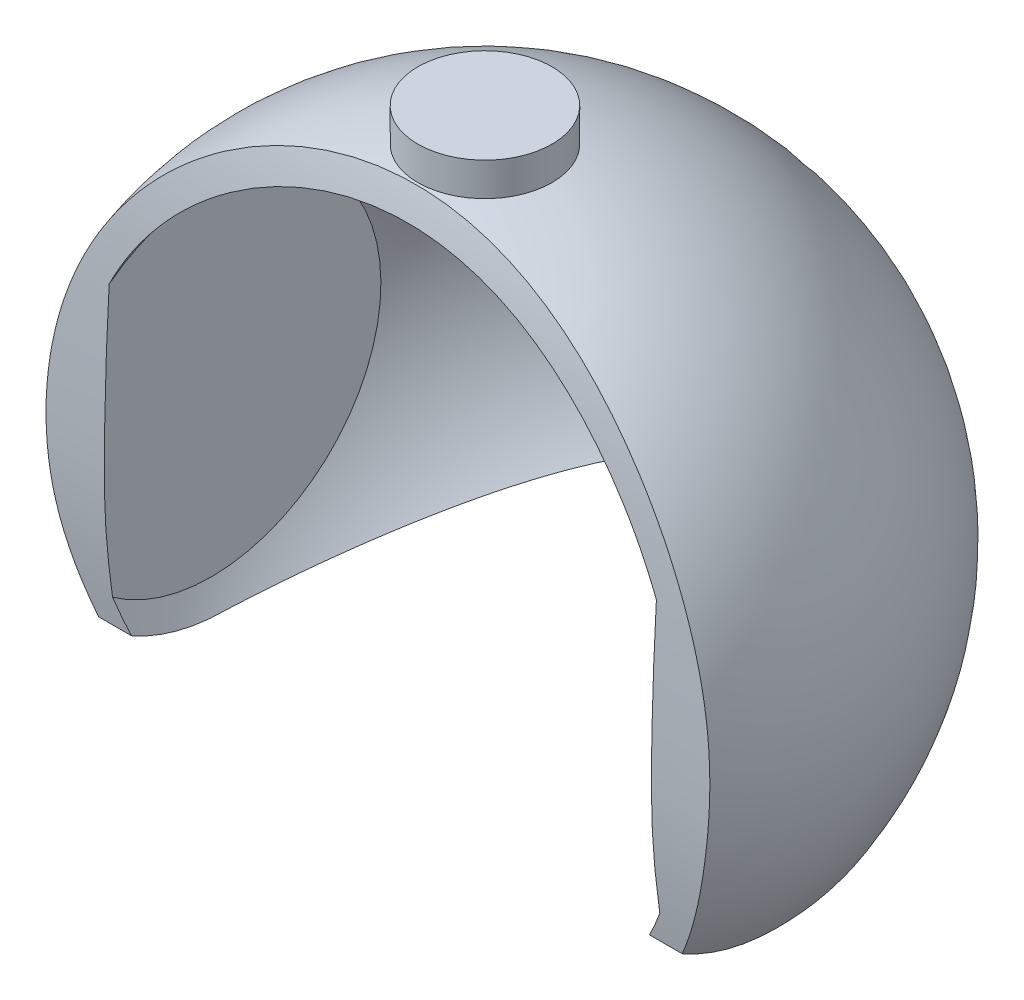
SolidWorks part; units mm, degrees
ref_plane "前视基准面" through (0, 0, 0) normal (0, 0, 1) x (1, 0, 0)
ref_plane "上视基准面" through (0, 0, 0) normal (0, 1, 0) x (1, 0, 0)
ref_plane "右视基准面" through (0, 0, 0) normal (1, 0, 0) x (0, 0, -1)
sketch "草图1" plane through (0, 0, 0) normal (0, 0, 1) x (1, 0, 0)
  line L0 (0, 0) -> (65, 0) construction
  line L1 (0, 0) -> (-65, 0) construction
  line L2 (65, 0) -> (-65, 0)
  arc A0 (65, 0) -> (-65, 0) centre (0, 0) ccw
  dimension "D1" = 130
revolve "旋转1" add sketch "草图1" angle 360 about L2
sketch "草图2" plane through (0, 0, 0) normal (1, 0, 0) x (0, 0, -1)
  circle A0 centre (0, 0) radius 65 construction
  arc A1 (-12.8963, 63.7078) -> (-12.8963, -63.7078) centre (0, 0) ccw
  spline S0 degree 3 poles (-12.8963, 63.7078) (-18.0688, 46.449) (-19.3163, 24.9438) (-20.0393, -0.9445) (-19.8545, -25.9273) (-14.0767, -46.8636) (-12.8963, -63.7078) knots 0 0 0 0 0.4176 0.500367 0.605328 1 1 1 1
extrude "切除-拉伸1" cut sketch "草图2" against normal mid plane 371
sketch "草图3" plane through (0, 0, 0) normal (0, 0, 1) x (1, 0, 0)
  line L0 (-61.8603, 0) -> (0, 0) construction
  line L1 (0, 0) -> (61.8603, 0) construction
  line L2 (51, 0) -> (51, 31.607)
  line L3 (0, 0) -> (0, 27.5389) construction
  line L4 (-51, 0) -> (-51, 31.607)
  line L5 (-51, 0) -> (51, 0)
  arc A0 (51, 31.607) -> (-51, 31.607) centre (0, 0) ccw
  spline S0 degree 3 poles (4.1719, 63.7078) (-4.1719, 63.7078) (-8.2647, 63.2762) (-14.2923, 62.0132) (-16.2827, 61.4887) (-19.24, 60.5436) (-20.2228, 60.2013) (-22.1571, 59.4713) (-23.111, 59.0829) (-27.8166, 57.027) (-31.3776, 55.0203) (-35.5847, 52.0644) (-36.4146, 51.4499) (-38.0458, 50.178) (-38.8424, 49.5243) (-41.177, 47.511) (-42.6598, 46.0995) (-45.4829, 43.141) (-46.8233, 41.5941) (-48.7269, 39.1715) (-49.3435, 38.3469) (-50.5407, 36.6631) (-51.1226, 35.8015) (-53.9156, 31.4438) (-55.7898, 27.7915) (-58.0721, 22.0703) (-58.744, 20.1224) (-59.6133, 17.1375) (-59.8805, 16.1293) (-60.363, 14.1103) (-60.5786, 13.0986) (-61.5302, 8.0293) (-61.8873, 3.939) (-61.8523, -1.2168) (-61.821, -2.2501) (-61.7104, -4.3211) (-61.6308, -5.3615) (-61.3231, -8.461) (-61.0268, -10.503) (-59.8852, -16.5579) (-58.794, -20.5006) (-56.9618, -25.3084) (-56.5706, -26.2662) (-55.747, -28.1513) (-55.3142, -29.08) (-53.9525, -31.8251) (-52.9605, -33.6007) (-50.8047, -37.0439) (-49.6409, -38.7116) (-47.7612, -41.1308) (-47.1123, -41.9234) (-45.7686, -43.4807) (-45.0714, -44.2476) (-41.5028, -47.9736) (-38.3823, -50.6178) (-33.3157, -54.0957) (-31.5621, -55.173) (-28.8323, -56.6625) (-27.9042, -57.1385) (-26.0361, -58.0371) (-25.0937, -58.4612) (-20.341, -60.4582) (-16.4095, -61.6643) (-11.3351, -62.6842) (-10.3108, -62.8638) (-8.2515, -63.1719) (-7.2222, -63.2996) (-4.1351, -63.6057) (-2.0783, -63.7071) (2.0329, -63.7085) (4.0873, -63.6086) (7.1671, -63.3059) (8.1934, -63.1795) (10.2453, -62.8746) (11.2737, -62.6955) (16.3646, -61.6773) (20.295, -60.4729) (25.979, -58.0915) (27.8381, -57.2012) (30.5713, -55.7153) (31.4741, -55.1941) (33.2394, -54.1135) (34.1046, -53.5528) (38.3446, -50.6489) (41.4635, -48.0074) (45.0185, -44.3047) (45.7121, -43.5439) (47.0643, -41.9811) (47.7186, -41.1838) (49.6103, -38.7544) (50.7798, -37.0812) (52.944, -33.6296) (53.9385, -31.8513) (55.3025, -29.1046) (55.7358, -28.1758) (56.56, -26.2915) (56.9516, -25.3338) (58.7878, -20.5217) (59.881, -16.5757) (61.0247, -10.516) (61.3216, -8.4725) (61.63, -5.3708) (61.7098, -4.3307) (61.8206, -2.2603) (61.852, -1.2272) (61.8879, 3.9274) (61.5317, 8.0175) (60.5808, 13.0876) (60.3654, 14.0995) (59.8832, 16.1189) (59.6161, 17.1274) (58.7471, 20.113) (58.0753, 22.0613) (55.7934, 27.7839) (53.9194, 31.4372) (51.1262, 35.7961) (50.5442, 36.6579) (49.3473, 38.3418) (48.7308, 39.1663) (46.8282, 41.5882) (45.489, 43.1342) (42.6693, 46.0901) (41.1888, 47.5) (38.8589, 49.5105) (38.0641, 50.1632) (36.4369, 51.4331) (35.6039, 52.0504) (31.3913, 55.0125) (27.8345, 57.0164) (22.2126, 59.4768) (20.2906, 60.2054) (17.3311, 61.1548) (16.3313, 61.4473) (14.3291, 61.9772) (13.3238, 62.2155) (8.2766, 63.2759) (4.1719, 63.7078) (-4.1719, 63.7078) (-8.2647, 63.2762) knots -0.03125 -0.03125 0 0 0.03125 0.03125 0.046875 0.046875 0.054687 0.054687 0.0625 0.0625 0.09375 0.09375 0.101562 0.101562 0.109375 0.109375 0.125 0.125 0.140625 0.140625 0.148437 0.148437 0.15625 0.15625 0.1875 0.1875 0.203125 0.203125 0.210937 0.210937 0.21875 0.21875 0.25 0.25 0.257812 0.257812 0.265625 0.265625 0.28125 0.28125 0.3125 0.3125 0.320312 0.320312 0.328125 0.328125 0.34375 0.34375 0.359375 0.359375 0.367187 0.367187 0.375 0.375 0.40625 0.40625 0.421875 0.421875 0.429687 0.429687 0.4375 0.4375 0.46875 0.46875 0.476562 0.476562 0.484375 0.484375 0.5 0.5 0.515625 0.515625 0.523437 0.523437 0.53125 0.53125 0.5625 0.5625 0.578125 0.578125 0.585937 0.585937 0.59375 0.59375 0.625 0.625 0.632812 0.632812 0.640625 0.640625 0.65625 0.65625 0.671875 0.671875 0.679687 0.679687 0.6875 0.6875 0.71875 0.71875 0.734375 0.734375 0.742187 0.742187 0.75 0.75 0.78125 0.78125 0.789062 0.789062 0.796875 0.796875 0.8125 0.8125 0.84375 0.84375 0.851562 0.851562 0.859375 0.859375 0.875 0.875 0.890625 0.890625 0.898437 0.898437 0.90625 0.90625 0.9375 0.9375 0.953125 0.953125 0.960937 0.960937 0.96875 0.96875 1 1 1.03125 1.03125 1.046875 only from (0, 63.7078) to (0, 63.7078) construction
  dimension "D1" = 120
  dimension "D2" = 51
revolve "切除-旋转1" cut sketch "草图3" angle 360 about L0
sketch "草图5" plane through (0, 0, 0) normal (1, 0, 0) x (0, 0, -1)
  line L0 (-17.9087, -30.7747) -> (-28.108, -58.6084)
  circle A0 centre (0, 0) radius 35.6062
  arc A1 (-12.8963, -63.7078) -> (-12.8963, 63.7078) centre (0, 0) ccw construction
  circle A2 centre (0, 0) radius 65
  spline S0 degree 3 poles (0, -35.6062) (22.5249, -36.1818) (48.5863, -29.4917) (63.9178, -11.8114) knots 0 0 0 0 1 1 1 1
  dimension "D1" = 130
extrude "切除-拉伸2" cut sketch "草图5" against normal mid plane 371 contours S0 A0 L0 A2
ref_plane "基准面1" through (0, 70, 0) normal (0, 1, 0) x (1, 0, 0)
sketch "草图8" plane through (0, 70, 0) normal (0, 1, 0) x (1, 0, 0)
  circle A0 centre (0, 0) radius 12.5
  dimension "D1" = 25
extrude "凸台-拉伸3" add sketch "草图8" against normal up to surface (6.2132 mm away)
